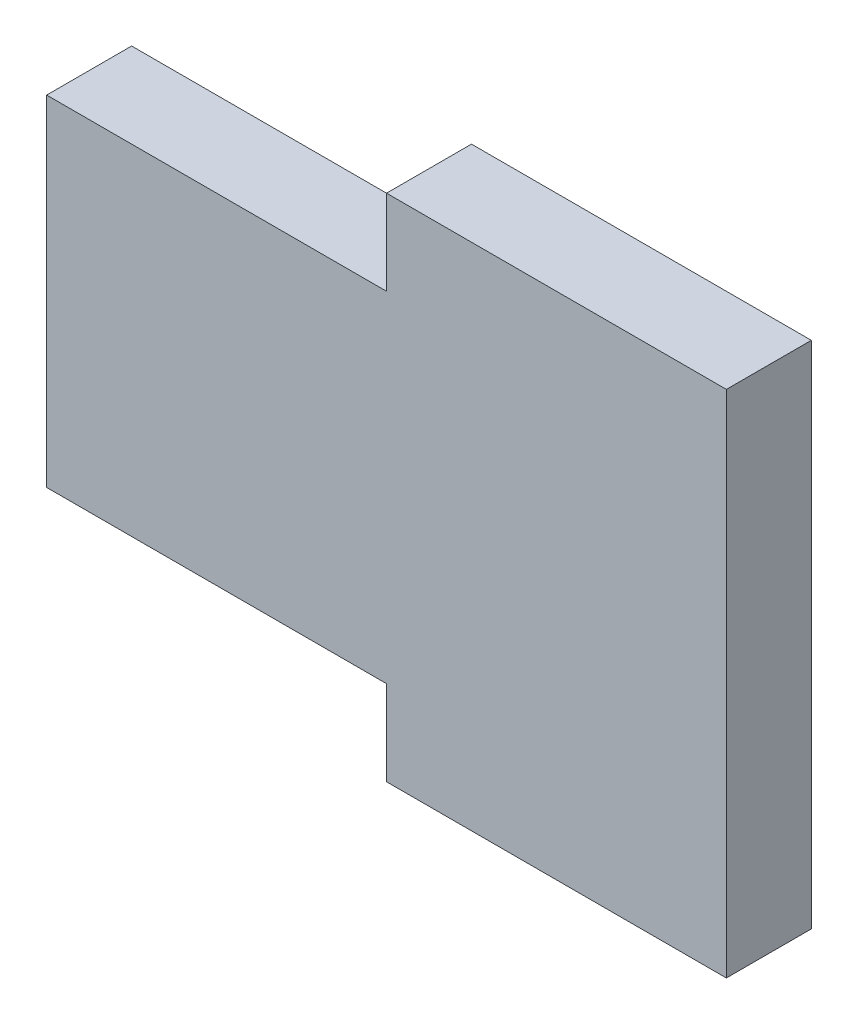
SolidWorks part; units mm, degrees
ref_plane "Front Plane" through (0, 0, 0) normal (0, 0, 1) x (1, 0, 0)
ref_plane "Top Plane" through (0, 0, 0) normal (0, 1, 0) x (1, 0, 0)
ref_plane "Right Plane" through (0, 0, 0) normal (1, 0, 0) x (0, 0, -1)
sketch "Sketch1" plane through (0, 0, 0) normal (0, 0, 1) x (1, 0, 0)
  line L1 (288.925, 0) -> (276.225, 0)
  line L2 (288.925, 0) -> (288.925, -19.05)
  line L3 (288.925, -19.05) -> (276.225, -19.05)
  line L4 (263.525, -3.175) -> (263.525, -15.875)
  line L7 (263.525, -3.175) -> (276.225, -3.175)
  line L8 (276.225, 0) -> (276.225, -3.175)
  line L11 (263.525, -15.875) -> (276.225, -15.875)
  line L12 (276.225, -19.05) -> (276.225, -15.875)
extrude "Boss-Extrude1" add sketch "Sketch1" along normal blind 3.175 contours L2 L3 L12 L11 L4 L7 L8 L1
